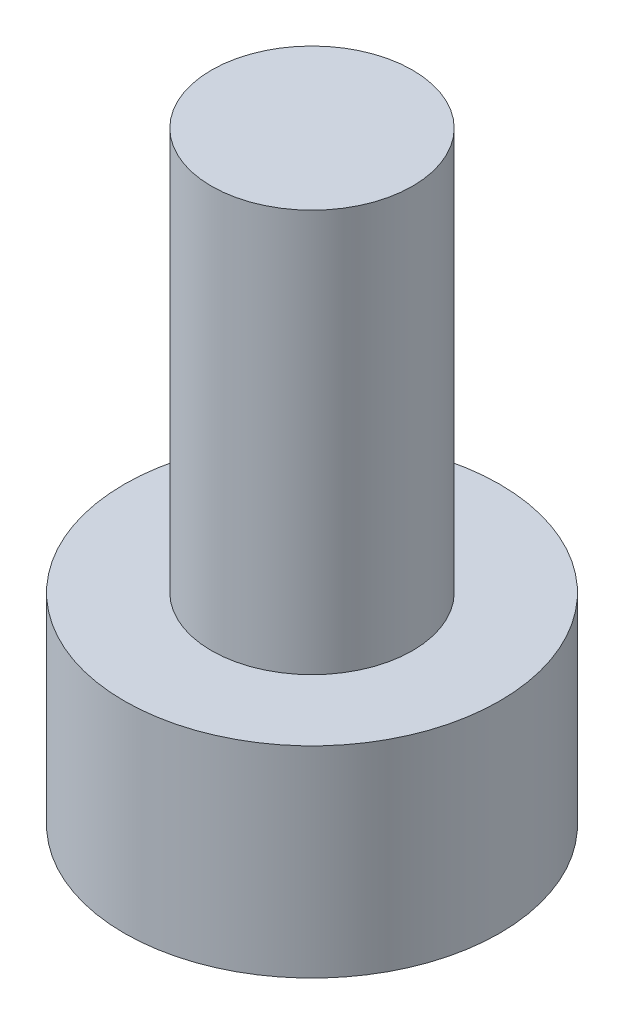
SolidWorks part; units mm, degrees
ref_plane "前视基准面" through (0, 0, 0) normal (0, 0, 1) x (1, 0, 0)
ref_plane "上视基准面" through (0, 0, 0) normal (0, 1, 0) x (1, 0, 0)
ref_plane "右视基准面" through (0, 0, 0) normal (1, 0, 0) x (0, 0, -1)
other "Configuration Table"
sketch "草图1" plane through (0, 0, 0) normal (0, 1, 0) x (1, 0, 0)
  circle A0 centre (0, 0) radius 2.8
  dimension "D1" = 5.6
extrude "凸台-拉伸1" add sketch "草图1" along normal blind 3
sketch "草图2" plane through (0, 3, 0) normal (0, 1, 0) x (1, 0, 0)
  circle A0 centre (0, 0) radius 1.5
  dimension "D1" = 3
extrude "凸台-拉伸2" add sketch "草图2" along normal blind 6
sketch "草图3" plane through (0, 0, 0) normal (0, -1, 0) x (1, 0, 0)
  line L1 (0, 1.4434) -> (-1.25, 0.7217)
  line L2 (-1.25, 0.7217) -> (-1.25, -0.7217)
  line L3 (-1.25, -0.7217) -> (0, -1.4434)
  line L4 (0, -1.4434) -> (1.25, -0.7217)
  line L5 (1.25, -0.7217) -> (1.25, 0.7217)
  line L6 (1.25, 0.7217) -> (0, 1.4434)
  circle A0 centre (0, 0) radius 1.25 construction
  dimension "D1" = 2.5
extrude "切除-拉伸1" cut sketch "草图3" against normal blind 1
